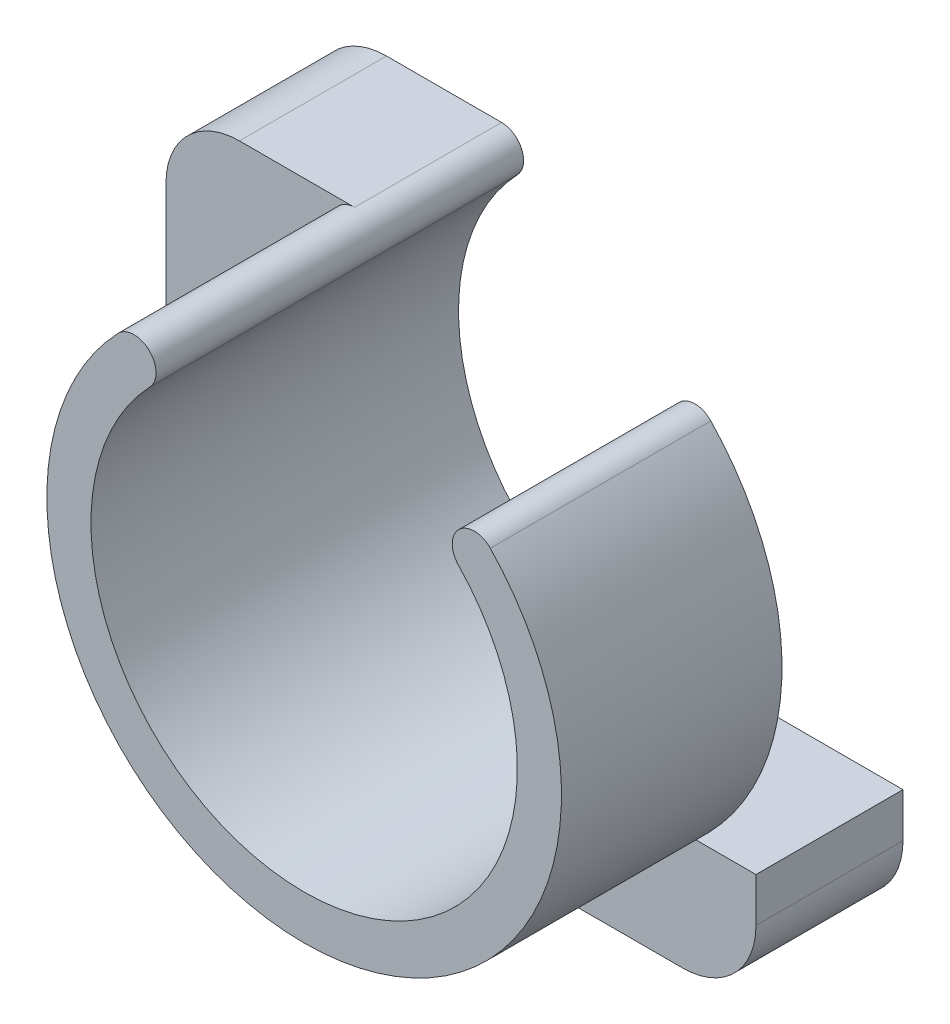
SolidWorks part; units mm, degrees
ref_plane "Front Plane" through (0, 0, 0) normal (0, 0, 1) x (1, 0, 0)
ref_plane "Top Plane" through (0, 0, 0) normal (0, 1, 0) x (1, 0, 0)
ref_plane "Right Plane" through (0, 0, 0) normal (1, 0, 0) x (0, 0, -1)
sketch "Sketch1" plane through (0, 0, 0) normal (0, 0, 1) x (1, 0, 0)
  line L0 (-2, -13.3953) -> (-2, 4.1047) construction
  circle A0 centre (-2, -13.3953) radius 14.5
  circle A1 centre (-2, -13.3953) radius 14
  circle A2 centre (-2, -13.3953) radius 14
  circle A3 centre (-2, -13.3953) radius 17.5
  circle A4 centre (9.5733, -2.3472) radius 1.5
  circle A5 centre (-13.5733, -2.3472) radius 1.5
  point P12 (11.8346, -3.5158)
  point P13 (10.2966, -1.6567)
  dimension "D1" = 0
  dimension "D2" = 0.5
  dimension "D3" = 3
extrude "Boss-Extrude1" add sketch "Sketch1" along normal blind 15 from offset 10 contours A0 A5 A3 A4 | A4 | A5 A3
sketch "Sketch2" plane through (0, 0, 0) normal (0, 0, 1) x (1, 0, 0)
  line L0 (-10.4, -25.4953) -> (15.8, -25.4953) construction
  line L1 (-11.4, -0.8472) -> (-26.4, -0.8472)
  line L2 (-11.4, -0.8472) -> (-11.4, -34.4953)
  line L3 (-11.4, -34.4953) -> (-26.4, -34.4953)
  line L4 (-26.4, -0.8472) -> (-26.4, -34.4953)
  line L5 (-11.4, -34.4953) -> (13.7294, -34.4953)
  line L6 (-11.4, -34.4953) -> (-11.4, -26.4953)
  line L7 (-11.4, -26.4953) -> (13.7294, -26.4953)
  line L8 (13.7294, -34.4953) -> (13.7294, -26.4953)
  line L9 (-10.4, -1.2953) -> (-10.4, -25.4953) construction
  arc A0 (-12.4883, -3.3829) -> (-14.6583, -1.3114) centre (-13.5733, -2.3472) ccw construction
  arc A5 (-12.4883, -3.3829) -> (8.4883, -3.3829) centre (-2, -13.3953) ccw
  arc A6 (-12.4883, -3.3829) -> (-14.6583, -1.3114) centre (-13.5733, -2.3472) ccw
  arc A7 (-14.6583, -1.3114) -> (10.6583, -1.3114) centre (-2, -13.3953) ccw
  arc A8 (10.6583, -1.3114) -> (8.4883, -3.3829) centre (9.5733, -2.3472) ccw
  arc A9 (-12.4883, -3.3829) -> (8.4883, -3.3829) centre (-2, -13.3953) ccw
  arc A10 (-12.4883, -3.3829) -> (-14.6583, -1.3114) centre (-13.5733, -2.3472) ccw
  arc A11 (-14.6583, -1.3114) -> (10.6583, -1.3114) centre (-2, -13.3953) ccw
  arc A12 (10.6583, -1.3114) -> (8.4883, -3.3829) centre (9.5733, -2.3472) ccw
  point P7 (12.3328, -35.8667)
  dimension "D1" = 1
  dimension "D2" = 1
  dimension "D3" = 8
  dimension "D4" = 15
  dimension "D5" = 0
extrude "Boss-Extrude3" add sketch "Sketch2" along normal up to surface (10 mm away) contours A10 A11 L2 A9 | A11 A10 L1 L4 L3 L6 | A11 L6 L5 L8 L7 | L2 A11 L7 A9
fillet "Fillet1" radius 5 3 edges at (13.7294, -34.4953, 5) (-26.4, -34.4953, 5) (-26.4, -0.8472, 5)
sketch "Sketch4" plane through (0, 0, 10) normal (0, 0, -1) x (-1, 0, 0)
  line L2 (8.2161, -26.4953) -> (11.4, -26.4953)
  line L3 (11.4, -26.4953) -> (11.4, -24.4356)
  line L4 (8.2161, -26.4953) -> (11.4, -26.4953)
  line L5 (11.4, -26.4953) -> (11.4, -24.4356)
  arc A1 (8.2161, -26.4953) -> (11.4, -24.4356) centre (2, -13.3953) ccw
  arc A2 (8.2161, -26.4953) -> (11.4, -24.4356) centre (2, -13.3953) ccw
  dimension "D1" = 0
extrude "Boss-Extrude4" add sketch "Sketch4" along normal up to surface (10 mm away) up to face at (-9.0007, -20.8949, 0)
